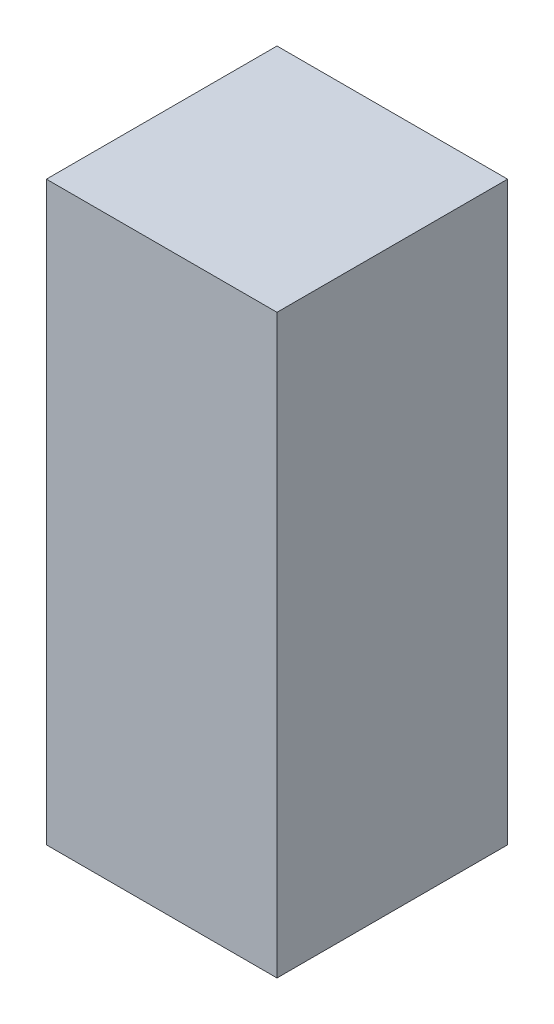
SolidWorks part; units mm, degrees
ref_plane "前基準面" through (0, 0, 0) normal (0, 0, 1) x (1, 0, 0)
ref_plane "上基準面" through (0, 0, 0) normal (0, 1, 0) x (1, 0, 0)
ref_plane "右基準面" through (0, 0, 0) normal (1, 0, 0) x (0, 0, -1)
sketch "草圖1" plane through (0, 0, 0) normal (0, 1, 0) x (1, 0, 0)
  line L1 (-10, 10) -> (10, 10)
  line L2 (-10, 10) -> (-10, -10)
  line L3 (-10, -10) -> (10, -10)
  line L4 (10, 10) -> (10, -10)
  line L5 (0, -10) -> (0, 10) construction
  line L6 (-10, 0) -> (10, 0) construction
  point P0 (0, 0)
  dimension "D1" = 20
  dimension "D2" = 20
extrude "填料-伸長1" add sketch "草圖1" along normal blind 50
